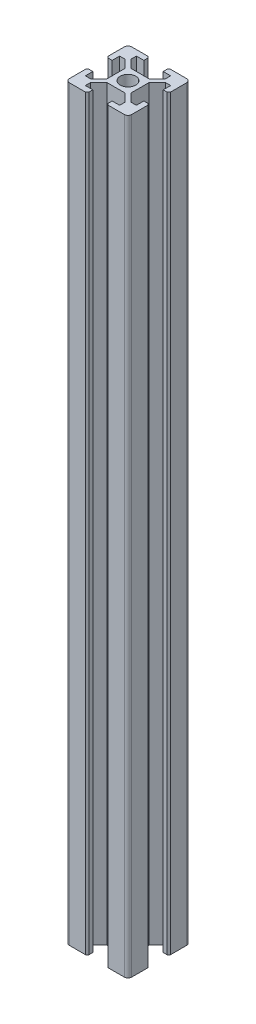
SolidWorks part; units mm, degrees
ref_plane "前视基准面" through (0, 0, 0) normal (0, 0, 1) x (1, 0, 0)
ref_plane "上视基准面" through (0, 0, 0) normal (0, 1, 0) x (1, 0, 0)
ref_plane "右视基准面" through (0, 0, 0) normal (1, 0, 0) x (0, 0, -1)
sketch "草图1" plane through (0, 0, 0) normal (0, 1, 0) x (1, 0, 0)
  line L0 (-16.4295, 0) -> (16.9006, 0) construction
  line L1 (0, 16.3993) -> (0, -16.4048) construction
  line L2 (5.5, 8.2) -> (3.1, 8.2015)
  line L3 (-2.9, 3.9) -> (2.9, 3.9)
  line L4 (-3.9, 2.9) -> (-3.9, -2.9)
  line L5 (-2.9, -3.9) -> (2.9, -3.9)
  line L6 (3.9, 2.9) -> (3.9, -2.9)
  line L8 (-3.9, -3.9) -> (3.9, 3.9) construction
  line L9 (10, -3.6) -> (9.5, -3.1)
  line L10 (10, -3.6) -> (10, -8.8)
  line L11 (3.6, -10) -> (8.8, -10)
  line L12 (3.6, -10) -> (3.1, -9.5)
  line L13 (3.1, -9.5) -> (3.1, -8.2015)
  line L14 (-3.9, -3.9) -> (10, 10) construction
  line L15 (5.5, -8.2) -> (3.1, -8.2015)
  line L16 (5.5, -8.2) -> (5.5, -6.5)
  line L17 (5.5, -6.5) -> (2.9, -3.9)
  line L18 (6.5, -5.5) -> (3.9, -2.9)
  line L19 (8.2, -5.5) -> (6.5, -5.5)
  line L20 (8.2, -5.5) -> (8.2015, -3.1)
  line L21 (5.5, 8.2) -> (5.5, 6.5)
  line L22 (9.5, -3.1) -> (8.2015, -3.1)
  line L23 (-3.6, -10) -> (-3.1, -9.5)
  line L24 (-3.6, -10) -> (-8.8, -10)
  line L25 (-10, -3.6) -> (-10, -8.8)
  line L26 (3.1, 9.5) -> (3.1, 8.2015)
  line L27 (5.5, 6.5) -> (2.9, 3.9)
  line L28 (-10, -3.6) -> (-9.5, -3.1)
  line L29 (3.6, 10) -> (3.1, 9.5)
  line L30 (3.6, 10) -> (8.8, 10)
  line L31 (6.5, 5.5) -> (3.9, 2.9)
  line L32 (-9.5, -3.1) -> (-8.2015, -3.1)
  line L33 (8.2, 5.5) -> (6.5, 5.5)
  line L34 (8.2, 5.5) -> (8.2015, 3.1)
  line L35 (9.5, 3.1) -> (8.2015, 3.1)
  line L36 (10, 3.6) -> (9.5, 3.1)
  line L37 (10, 3.6) -> (10, 8.8)
  line L38 (-8.2, -5.5) -> (-8.2015, -3.1)
  line L39 (-8.2, -5.5) -> (-6.5, -5.5)
  line L40 (-6.5, -5.5) -> (-3.9, -2.9)
  line L41 (-5.5, -6.5) -> (-2.9, -3.9)
  line L42 (-5.5, -8.2) -> (-5.5, -6.5)
  line L43 (-5.5, -8.2) -> (-3.1, -8.2015)
  line L44 (-3.1, -9.5) -> (-3.1, -8.2015)
  line L45 (-10, 3.6) -> (-9.5, 3.1)
  line L46 (-10, 3.6) -> (-10, 8.8)
  line L47 (-3.6, 10) -> (-8.8, 10)
  line L48 (-3.6, 10) -> (-3.1, 9.5)
  line L49 (-3.1, 9.5) -> (-3.1, 8.2015)
  line L50 (-5.5, 8.2) -> (-3.1, 8.2015)
  line L51 (-5.5, 8.2) -> (-5.5, 6.5)
  line L52 (-5.5, 6.5) -> (-2.9, 3.9)
  line L53 (-6.5, 5.5) -> (-3.9, 2.9)
  line L54 (-8.2, 5.5) -> (-6.5, 5.5)
  line L55 (-8.2, 5.5) -> (-8.2015, 3.1)
  line L56 (-9.5, 3.1) -> (-8.2015, 3.1)
  arc A0 (8.8, 10) -> (10, 8.8) centre (8.8, 8.8) cw
  arc A1 (10, -8.8) -> (8.8, -10) centre (8.8, -8.8) cw
  arc A2 (-8.8, -10) -> (-10, -8.8) centre (-8.8, -8.8) cw
  arc A3 (-10, 8.8) -> (-8.8, 10) centre (-8.8, 8.8) cw
  circle A4 centre (0, 0) radius 2.5
  point P5 (0, 0)
  point P10 (0, 0)
  point P15 (0, 0)
  point P20 (5.5, 6.5)
  point P23 (0, 0)
  point P27 (0, 0)
  point P31 (0, 0)
  point P35 (0, 0)
  point P81 (0, 0)
  dimension "D2" = 1.2
  dimension "D10" = 5
  dimension "D1" = 7.8
  dimension "D3" = 4
  dimension "D4" = 20
  dimension "D6" = 3.1
  dimension "D7" = 3.6
  dimension "D8" = 11
  dimension "D9" = 1.7
  dimension "D11" = 5.8
  dimension "D12" = 3.9
  dimension "D13" = 0.5
  dimension "D14" = 3.9
  dimension "D5" = 4
extrude "凸台-拉伸1" add sketch "草图1" along normal blind 240
